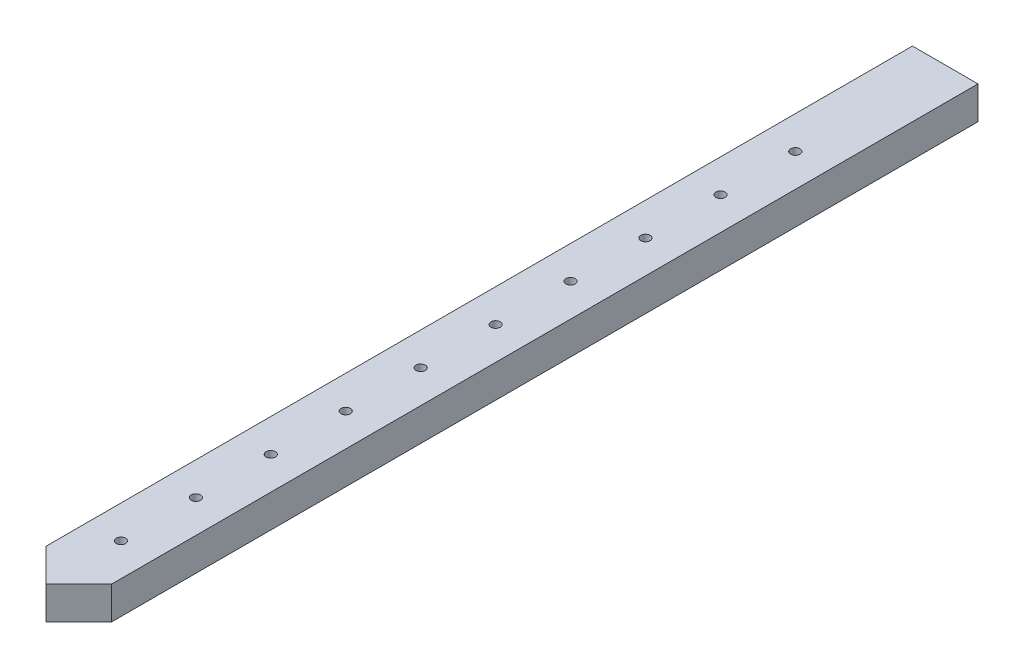
SolidWorks part; units mm, degrees
ref_plane "Front Plane" through (0, 0, 0) normal (0, 0, 1) x (1, 0, 0)
ref_plane "Top Plane" through (0, 0, 0) normal (0, 1, 0) x (1, 0, 0)
ref_plane "Right Plane" through (0, 0, 0) normal (1, 0, 0) x (0, 0, -1)
sketch "Sketch1" plane through (0, 0, 0) normal (0, 0, 1) x (1, 0, 0)
  line L1 (-44.45, -22.225) -> (44.45, -22.225)
  line L2 (-44.45, -22.225) -> (-44.45, 22.225)
  line L3 (-44.45, 22.225) -> (44.45, 22.225)
  line L4 (44.45, -22.225) -> (44.45, 22.225)
  line L5 (-44.45, -22.225) -> (44.45, 22.225) construction
  line L6 (-44.45, 22.225) -> (44.45, -22.225) construction
  point P0 (0, 0)
  dimension "D1" = 44.45
  dimension "D2" = 88.9
extrude "Boss-Extrude1" add sketch "Sketch1" along normal blind 1219.2
sketch "Sketch2" plane through (0, 22.225, 0) normal (0, 1, 0) x (1, 0, 0)
  line L0 (0, -1219.2) -> (0, 0) construction
  line L1 (44.45, -1219.2) -> (-44.45, -1219.2) construction
  line L2 (0, -1219.2) -> (-44.45, -1174.75)
  line L3 (-44.45, -1219.2) -> (-44.45, 0) construction
  line L4 (-44.45, -1174.75) -> (-44.45, -1219.2)
  line L5 (-44.45, -1219.2) -> (0, -1219.2)
  line L6 (44.45, -1219.2) -> (44.45, -1174.75)
  line L7 (44.45, -1219.2) -> (44.45, 0) construction
  line L8 (0, -1219.2) -> (44.45, -1174.75)
  line L9 (0, -1219.2) -> (44.45, -1219.2)
  line M6 (-44.45, 0) -> (-44.45, -1219.2)
  line M7 (-44.45, -1219.2) -> (44.45, -1219.2)
  line M8 (44.45, -1219.2) -> (44.45, 0)
  dimension "D1" = 45
  dimension "D2" = 45
extrude "Cut-Extrude1" cut sketch "Sketch2" against normal through all contours L2 M7 M6 | L8 M7 M8
sketch "Sketch3" plane through (0, 22.225, 0) normal (0, 1, 0) x (1, 0, 0)
  line L0 (0, -1219.2) -> (0, 0) construction
  circle A0 centre (0, -1117.6) radius 6.35
  dimension "D1" = 12.7
  dimension "D2" = 101.6
extrude "Cut-Extrude2" cut sketch "Sketch3" against normal blind 22.225
sketch "Sketch4" plane through (0, 22.225, 0) normal (0, 1, 0) x (1, 0, 0)
  line L0 (-44.45, -1174.75) -> (44.45, -1174.75) construction
pattern_linear "LPattern1" count 10 spacing 101.6 along (0, 0, -1) of "Cut-Extrude2"
